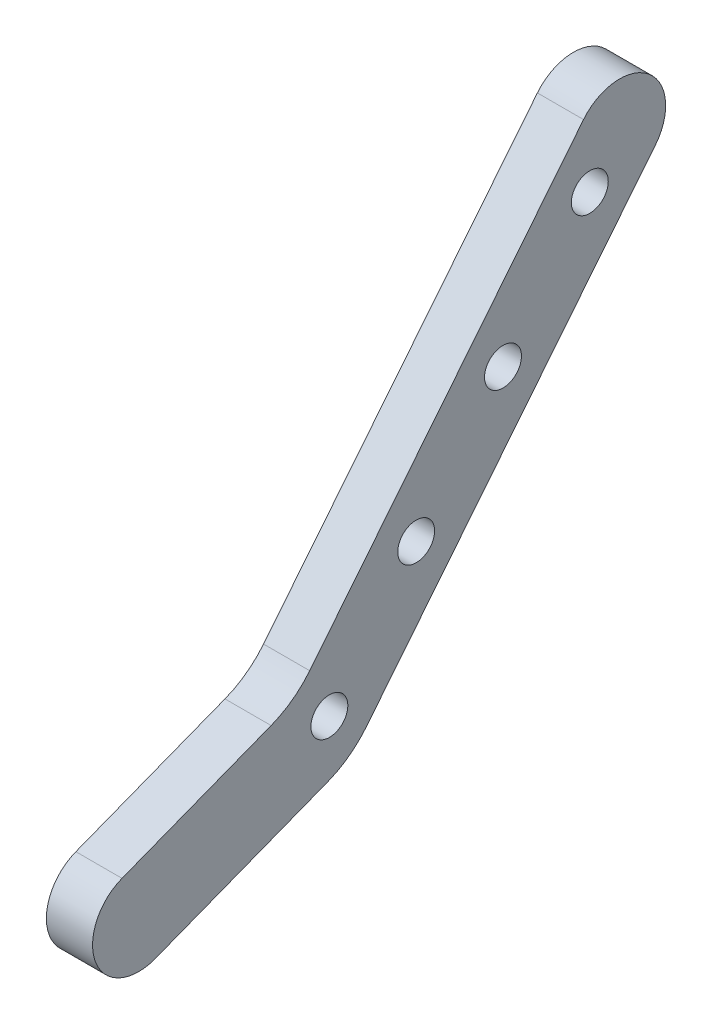
SolidWorks part; units mm, degrees
ref_plane "Front Plane" through (0, 0, 0) normal (0, 0, 1) x (1, 0, 0)
ref_plane "Top Plane" through (0, 0, 0) normal (0, 1, 0) x (1, 0, 0)
ref_plane "Right Plane" through (0, 0, 0) normal (1, 0, 0) x (0, 0, -1)
sketch "Sketch1" plane through (0, 0, 0) normal (1, 0, 0) x (0, 0, -1)
  line L6 (0, 0) -> (32.1834, 40) construction
  line L7 (0, 0) -> (-19.8982, -7.7102) construction
  line L8 (3.8956, -3.1344) -> (36.079, 36.8656)
  line L9 (-3.0558, 4.1782) -> (28.2878, 43.1344)
  line L10 (-3.0558, 4.1782) -> (-21.7047, -3.0479)
  line L11 (1.8065, -4.6622) -> (-18.0917, -12.3724)
  line L12 (-1.8065, 4.6622) -> (-21.7047, -3.0479) construction
  line L13 (-3.8956, 3.1344) -> (28.2878, 43.1344) construction
  line L14 (3.8956, -3.1344) -> (3.0558, -4.1782)
  line L15 (1.8065, -4.6622) -> (3.0558, -4.1782)
  arc A2 (-21.7047, -3.0479) -> (-18.0917, -12.3724) centre (-19.8982, -7.7102) ccw
  arc A3 (28.2878, 43.1344) -> (36.079, 36.8656) centre (32.1834, 40) cw
  dimension "D1" = 50
  dimension "D2" = 20
  dimension "D8" = 40
  dimension "D3" = 150
  dimension "D4" = 5
  dimension "D5" = 5
  dimension "D6" = 5
  dimension "D7" = 5
extrude "Boss-Extrude1" add sketch "Sketch1" along normal blind 5
sketch "Sketch2" plane through (5, 0, 0) normal (1, 0, 0) x (0, 0, -1)
  line L0 (0, 0) -> (32.1834, 40) construction
  circle A0 centre (28.965, 36) radius 2
  circle A1 centre (19.562, 24.3131) radius 2
  circle A2 centre (10.1589, 12.6263) radius 2
  circle A3 centre (0.7559, 0.9394) radius 2
  dimension "D1" = 4
  dimension "D2" = 4
  dimension "D3" = 4
extrude "Cut-Extrude1" cut sketch "Sketch2" against normal blind 5
fillet "Fillet1" radius 10 1 edges at (2.5, 4.1782, 3.0558)
fillet "Fillet2" radius 10 1 edges at (2.5, -4.1782, -3.0558)
